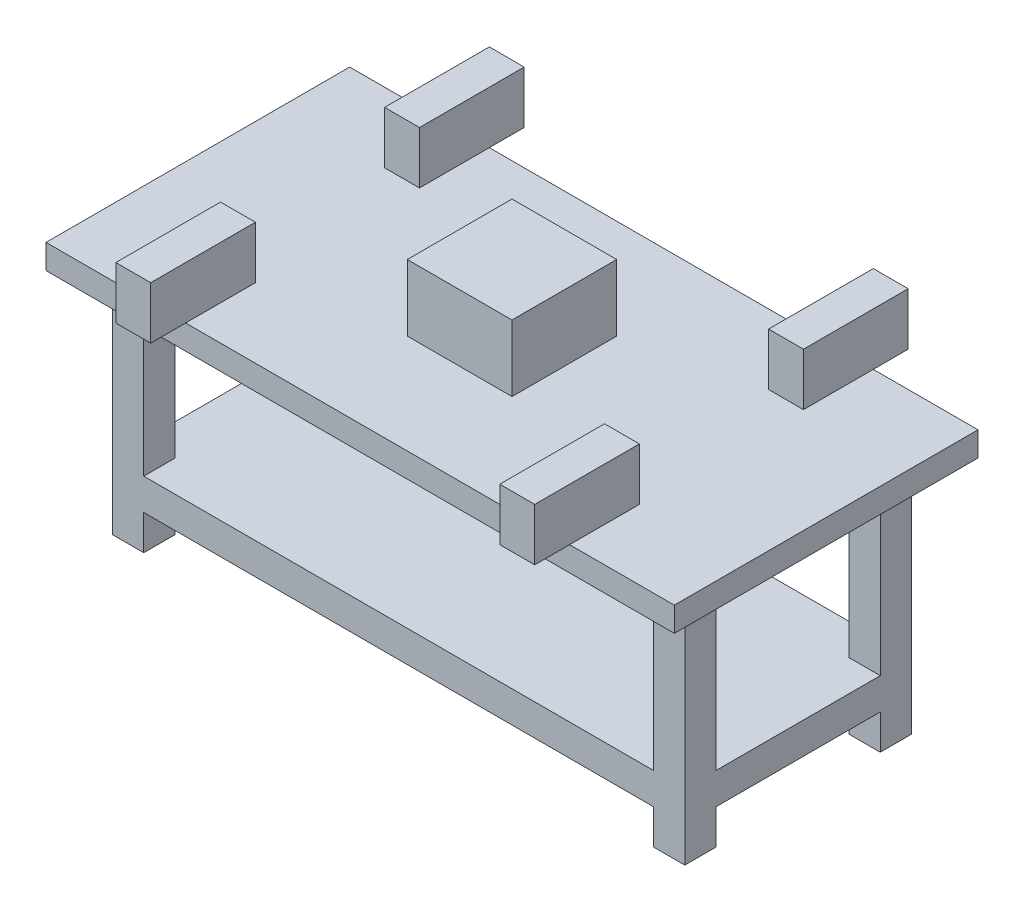
SolidWorks part; units mm, degrees
ref_plane "正面" through (0, 0, 0) normal (0, 0, 1) x (1, 0, 0)
ref_plane "平面" through (0, 0, 0) normal (0, 1, 0) x (1, 0, 0)
ref_plane "右側面" through (0, 0, 0) normal (1, 0, 0) x (0, 0, -1)
sketch "ｽｹｯﾁ1" plane through (0, 0, 0) normal (0, 1, 0) x (1, 0, 0)
  line L1 (0, 0) -> (1800, 0)
  line L2 (0, 0) -> (0, 870)
  line L3 (0, 870) -> (1800, 870)
  line L4 (1800, 0) -> (1800, 870)
  dimension "D1" = 1800
  dimension "D2" = 870
extrude "ﾎﾞｽ - 押し出し1" add sketch "ｽｹｯﾁ1" along normal blind 70
sketch "ｽｹｯﾁ2" plane through (0, 70, 0) normal (0, 1, 0) x (1, 0, 0)
  line L0 (0, 870) -> (0, 0) construction
  line L1 (300, 200) -> (400, 200)
  line L2 (300, 200) -> (300, -100)
  line L3 (300, -100) -> (400, -100)
  line L4 (400, 200) -> (400, -100)
  line L5 (1400, 200) -> (1500, 200)
  line L6 (1400, 200) -> (1400, -100)
  line L7 (1400, -100) -> (1500, -100)
  line L8 (1500, 200) -> (1500, -100)
  line L9 (1400, 970) -> (1500, 970)
  line L10 (1400, 970) -> (1400, 670)
  line L11 (1400, 670) -> (1500, 670)
  line L12 (1500, 970) -> (1500, 670)
  line L13 (300, 970) -> (400, 970)
  line L14 (300, 970) -> (300, 670)
  line L15 (300, 670) -> (400, 670)
  line L16 (400, 970) -> (400, 670)
  line L17 (1800, 0) -> (1800, 870) construction
  line L18 (0, 0) -> (1800, 0) construction
  line L19 (1800, 870) -> (0, 870) construction
  dimension "D1" = 300
  dimension "D2" = 300
  dimension "D3" = 300
  dimension "D4" = 300
  dimension "D5" = 100
  dimension "D6" = 100
  dimension "D7" = 100
  dimension "D8" = 100
  dimension "D9" = 300
  dimension "D10" = 300
  dimension "D11" = 300
  dimension "D12" = 300
  dimension "D13" = 100
  dimension "D14" = 100
  dimension "D15" = 100
  dimension "D16" = 100
extrude "ﾎﾞｽ - 押し出し2" add sketch "ｽｹｯﾁ2" along normal blind 150
sketch "ｽｹｯﾁ3" plane through (0, 70, 0) normal (0, 1, 0) x (1, 0, 0)
  line L0 (400, 0) -> (1400, 0) construction
  line L1 (750, 585) -> (1050, 585)
  line L2 (750, 585) -> (750, 285)
  line L3 (750, 285) -> (1050, 285)
  line L4 (1050, 585) -> (1050, 285)
  line L7 (1800, 0) -> (1800, 870) construction
  dimension "D1" = 300
  dimension "D2" = 300
  dimension "D3" = 285
  dimension "D4" = 750
extrude "ﾎﾞｽ - 押し出し3" add sketch "ｽｹｯﾁ3" along normal blind 190
sketch "ｽｹｯﾁ4" plane through (0, 0, 0) normal (0, -1, 0) x (-1, 0, 0)
  line L0 (0, 0) -> (-1800, 0) construction
  line L1 (-1720, 80) -> (-1630, 80)
  line L2 (-1720, 80) -> (-1720, 790)
  line L3 (-1720, 790) -> (-1630, 790)
  line L4 (-1630, 80) -> (-1630, 790)
  line L5 (-170, 80) -> (-80, 80)
  line L6 (-170, 80) -> (-170, 790)
  line L7 (-170, 790) -> (-80, 790)
  line L8 (-80, 80) -> (-80, 790)
  line L10 (-1800, 0) -> (-1800, 870) construction
  line L11 (-1800, 870) -> (0, 870) construction
  line L12 (0, 870) -> (0, 0) construction
  line L14 (-1630, 760) -> (-170, 760)
  line L15 (-1630, 760) -> (-1630, 670)
  line L16 (-1630, 670) -> (-170, 670)
  line L17 (-170, 760) -> (-170, 670)
  line L18 (-1630, 110) -> (-170, 110)
  line L19 (-1630, 110) -> (-1630, 200)
  line L20 (-1630, 200) -> (-170, 200)
  line L21 (-170, 110) -> (-170, 200)
  dimension "D1" = 90
  dimension "D2" = 90
  dimension "D3" = 80
  dimension "D4" = 80
  dimension "D5" = 80
  dimension "D6" = 80
  dimension "D7" = 80
  dimension "D8" = 80
  dimension "D9" = 90
  dimension "D10" = 90
  dimension "D11" = 120
  dimension "D12" = 120
extrude "ﾎﾞｽ - 押し出し4" add sketch "ｽｹｯﾁ4" along normal blind 70 contours L1 L4 L3 L2 | L4 L16 L6 L14 | L20 L4 L18 L6 | L5 L8 L7 L6
sketch "ｽｹｯﾁ5" plane through (0, -70, 0) normal (0, -1, 0) x (-1, 0, 0)
  line L0 (-1720, 80) -> (-1720, 790) construction
  line L1 (-1630, 110) -> (-1720, 110)
  line L2 (-1630, 110) -> (-1630, 200)
  line L3 (-1630, 200) -> (-1720, 200)
  line L4 (-1720, 110) -> (-1720, 200)
  line L6 (-1630, 670) -> (-1720, 670)
  line L7 (-1630, 670) -> (-1630, 760)
  line L8 (-1630, 760) -> (-1720, 760)
  line L9 (-1720, 670) -> (-1720, 760)
  line L10 (-170, 200) -> (-80, 200)
  line L11 (-170, 200) -> (-170, 110)
  line L12 (-170, 110) -> (-80, 110)
  line L13 (-80, 200) -> (-80, 110)
  line L14 (-170, 670) -> (-80, 670)
  line L15 (-170, 670) -> (-170, 760)
  line L16 (-170, 760) -> (-80, 760)
  line L17 (-80, 670) -> (-80, 760)
  dimension "D1" = 90
  dimension "D2" = 90
  dimension "D3" = 90
  dimension "D4" = 90
  dimension "D5" = 90
  dimension "D6" = 90
  dimension "D7" = 90
  dimension "D8" = 90
extrude "ﾎﾞｽ - 押し出し5" add sketch "ｽｹｯﾁ5" along normal blind 600
sketch "ｽｹｯﾁ6" plane through (0, 0, -200) normal (0, 0, -1) x (-1, 0, 0)
  line L0 (-1720, -670) -> (-1720, -70) construction
  line L1 (-1720, -570) -> (-1630, -570)
  line L2 (-1720, -570) -> (-1720, -480)
  line L3 (-1720, -480) -> (-1630, -480)
  line L4 (-1630, -570) -> (-1630, -480)
  line L5 (-1630, -670) -> (-1630, -70) construction
  line L6 (-170, -670) -> (-170, -70) construction
  line L7 (-170, -570) -> (-80, -570)
  line L8 (-170, -570) -> (-170, -480)
  line L9 (-170, -480) -> (-80, -480)
  line L10 (-80, -570) -> (-80, -480)
  line L11 (-80, -670) -> (-80, -70) construction
  line L12 (-80, -670) -> (-170, -670) construction
  line L13 (-1630, -670) -> (-1720, -670) construction
  dimension "D1" = 90
  dimension "D2" = 90
  dimension "D3" = 100
  dimension "D4" = 100
extrude "ﾎﾞｽ - 押し出し6" add sketch "ｽｹｯﾁ6" along normal up to next
sketch "ｽｹｯﾁ7" plane through (1630, 0, 0) normal (-1, 0, 0) x (0, 0, 1)
  line L0 (-110, -670) -> (-110, -70) construction
  line L1 (-760, -480) -> (-110, -480)
  line L2 (-760, -480) -> (-760, -570)
  line L3 (-760, -570) -> (-110, -570)
  line L4 (-110, -480) -> (-110, -570)
  line L5 (-760, -670) -> (-760, -70) construction
  line L6 (-670, -480) -> (-200, -480) construction
  line L7 (-670, -570) -> (-200, -570) construction
extrude "ﾎﾞｽ - 押し出し7" add sketch "ｽｹｯﾁ7" along normal up to next
